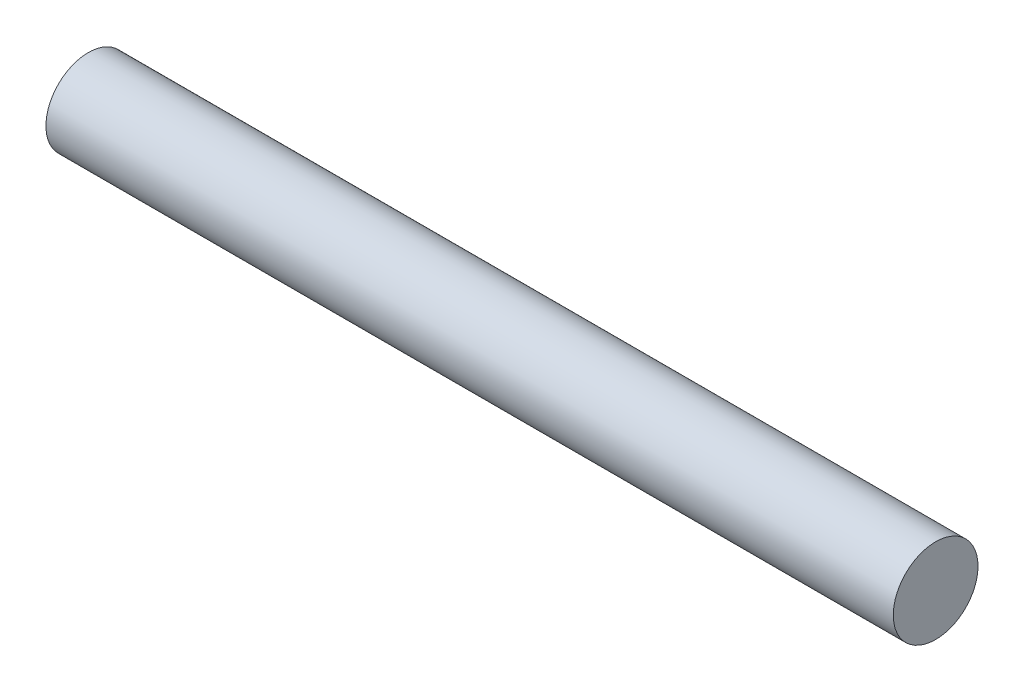
SolidWorks part; units mm, degrees
ref_plane "Alzado" through (0, 0, 0) normal (0, 0, 1) x (1, 0, 0)
ref_plane "Planta" through (0, 0, 0) normal (0, 1, 0) x (1, 0, 0)
ref_plane "Vista lateral" through (0, 0, 0) normal (1, 0, 0) x (0, 0, -1)
sketch "Croquis1" plane through (0, 0, 0) normal (1, 0, 0) x (0, 0, -1)
  circle A0 centre (0, 0) radius 1.5
  dimension "D1" = 3
extrude "Saliente-Extruir1" add sketch "Croquis1" along normal blind 30
